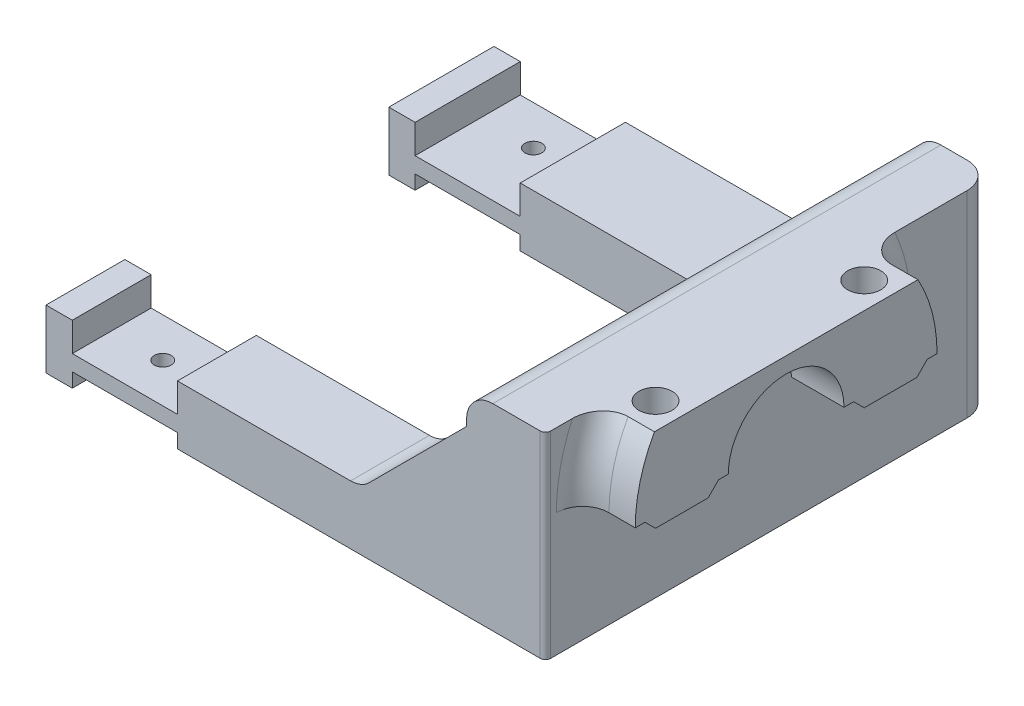
SolidWorks part; units mm, degrees
ref_plane "Plano frontal" through (0, 0, 0) normal (0, 0, 1) x (1, 0, 0)
ref_plane "Plano superior" through (0, 0, 0) normal (0, 1, 0) x (1, 0, 0)
ref_plane "Plano direito" through (0, 0, 0) normal (1, 0, 0) x (0, 0, -1)
sketch "Esboço1" plane through (0, 0, 0) normal (0, 1, 0) x (1, 0, 0)
  line L1 (10, -7.5) -> (-10, -7.5)
  line L2 (10, -7.5) -> (10, 7.5)
  line L3 (10, 7.5) -> (-10, 7.5)
  line L4 (-10, -7.5) -> (-10, 7.5)
  line L5 (10, -7.5) -> (-10, 7.5) construction
  line L6 (10, 7.5) -> (-10, -7.5) construction
  point P0 (0, 0)
  dimension "D1" = 20
  dimension "D2" = 15
extrude "Ressalto-extrusão1" add sketch "Esboço1" along normal mid plane 3
sketch "Esboço2" plane through (0, 0, 7.5) normal (0, 0, 1) x (1, 0, 0)
  line L0 (-10, 1.5) -> (-10, -1.5) construction
  line L6 (-10, -1.5) -> (10, -1.5) construction
  line L7 (-10, -4.2) -> (-15, -4.2)
  line L8 (-10, -4.2) -> (-10, 7)
  line L9 (-10, 7) -> (-15, 7)
  line L10 (-15, -4.2) -> (-15, 7)
  line L11 (-10, 1.5) -> (10, 1.5) construction
  dimension "D1" = 2.7
  dimension "D2" = 5.5
  dimension "D3" = 5
extrude "Ressalto-extrusão2" add sketch "Esboço2" against normal up to surface (15 mm away) up to face at (0, 0, -7.5)
sketch "Esboço3" plane through (0, 0, 7.5) normal (0, 0, 1) x (1, 0, 0)
  line L0 (10, 1.5) -> (10, -1.5) construction
  line L1 (10, -4.2) -> (80, -4.2)
  line L2 (10, -4.2) -> (10, 7)
  line L3 (10, 7) -> (80, 7)
  line L4 (80, -4.2) -> (80, 7)
  line L5 (-10, -1.5) -> (10, -1.5) construction
  line L6 (-10, 1.5) -> (10, 1.5) construction
  dimension "D1" = 2.7
  dimension "D2" = 5.5
  dimension "D3" = 70
extrude "Ressalto-extrusão3" add sketch "Esboço3" against normal up to surface (15 mm away) up to face at (-6.25, 0.7, -7.5)
sketch "Esboço4" plane through (0, 7, 0) normal (0, 1, 0) x (1, 0, 0)
  line L0 (-10, 77.7046) -> (-10, 57.7046) construction
  line L5 (80, 7.5) -> (65, 7.5)
  line L6 (80, 7.5) -> (80, 57.7)
  line L7 (80, 57.7) -> (65, 57.7) construction
  line L8 (65, 7.5) -> (65, 57.7)
  line L9 (65, 57.7) -> (-15, 57.7)
  line L10 (80, 57.7) -> (80, 77.7046)
  line L11 (80, 77.7046) -> (-15, 77.7046)
  line L12 (-15, 57.7) -> (-15, 77.7046)
  dimension "D1" = 50.2
  dimension "D2" = 15
  dimension "D3" = 5
  dimension "D4" = 20.0046
extrude "Ressalto-extrusão4" add sketch "Esboço4" against normal up to surface (11.2 mm away) up to face at (45, -4.2, 0)
sketch "Esboço5" plane through (0, 0, -77.7046) normal (0, 0, -1) x (-1, 0, 0)
  line L0 (-80, 7) -> (15, 7) construction
  line L1 (-10, 1.5) -> (10, 1.5)
  line L2 (-10, 1.5) -> (-10, 7)
  line L3 (-10, 7) -> (10, 7)
  line L4 (10, 1.5) -> (10, 7)
  line L5 (10, 7) -> (10, 1.5) construction
  line L6 (-80, -4.2) -> (15, -4.2) construction
  line L7 (-10, -1.5) -> (10, -1.5)
  line L8 (-10, -1.5) -> (-10, -4.2)
  line L9 (-10, -4.2) -> (10, -4.2)
  line L10 (10, -1.5) -> (10, -4.2)
  line L11 (10, -1.5) -> (10, -10.5) construction
extrude "Corte-extrusão1" cut sketch "Esboço5" against normal up to next
sketch "Esboço6" plane through (80, 0, 0) normal (1, 0, 0) x (0, 0, -1)
  line L0 (77.7046, 7) -> (-7.5, 7) construction
  line L1 (-0.4254, 7) -> (56.9746, 7)
  line L2 (-0.4254, 7) -> (-0.4254, 19.26)
  line L3 (-0.2682, 22.26) -> (56.8173, 22.26)
  line L4 (56.9746, 7) -> (56.9746, 19.26)
  line L5 (-0.4254, 19.26) -> (1.4246, 19.26) construction
  circle A0 centre (28.2746, 19.26) radius 28.7 construction
  arc A1 (-0.4254, 19.26) -> (-0.2682, 22.26) centre (28.2746, 19.26) cw
  arc A2 (56.9746, 19.26) -> (56.8173, 22.26) centre (28.2746, 19.26) ccw
  dimension "D1" = 3
extrude "Ressalto-extrusão5" add sketch "Esboço6" against normal up to surface (15 mm away) up to face at (65, 1.4, -32.6)
sketch "Esboço7" plane through (80, 0, 0) normal (1, 0, 0) x (0, 0, -1)
  line L0 (-0.4254, 19.26) -> (1.4246, 19.26)
  line L1 (3.4246, 17.26) -> (1.4246, 19.26) construction
  line L2 (1.4246, 19.26) -> (3.4246, 17.26)
  line L3 (3.4246, 17.26) -> (13.4246, 17.26)
  line L4 (13.4246, 17.26) -> (15.4246, 19.26)
  line L5 (15.4246, 19.26) -> (17.2746, 19.26)
  line L7 (56.8173, 22.26) -> (-0.2682, 22.26) construction
  line L8 (28.2746, 22.26) -> (28.2746, -4.2) construction
  line L9 (77.7046, -4.2) -> (-7.5, -4.2) construction
  line L11 (41.1246, 19.26) -> (39.2746, 19.26)
  line L12 (43.1246, 17.26) -> (41.1246, 19.26)
  line L13 (53.1246, 17.26) -> (43.1246, 17.26)
  line L14 (55.1246, 19.26) -> (53.1246, 17.26)
  line L15 (56.9746, 19.26) -> (55.1246, 19.26)
  line L16 (3.2208, 33.26) -> (53.3283, 33.26)
  arc A0 (39.2746, 19.26) -> (17.2746, 19.26) centre (28.2746, 19.26) ccw
  circle A1 centre (28.2746, 19.26) radius 11 construction
  arc A3 (-0.2682, 22.26) -> (-0.4254, 19.26) centre (28.2746, 19.26) ccw construction
  circle A7 centre (28.2746, 19.26) radius 28.7 construction
  arc A8 (3.2208, 33.26) -> (-0.4254, 19.26) centre (28.2746, 19.26) ccw
  arc A9 (56.9746, 19.26) -> (53.3283, 33.26) centre (28.2746, 19.26) ccw
  dimension "D1" = 3
extrude "Ressalto-extrusão6" add sketch "Esboço7" along normal blind 10
sketch "Esboço8" plane through (80, 0, 0) normal (-1, 0, 0) x (0, 0, 1)
  line L5 (0.2682, 22.26) -> (-56.8173, 22.26)
  line L8 (-56.8173, 22.26) -> (-38.8576, 22.26)
  line L9 (-17.6916, 22.26) -> (0.2682, 22.26)
  line L10 (-3.2208, 33.26) -> (-53.3283, 33.26)
  line L13 (-3.2208, 33.26) -> (-53.3283, 33.26)
  arc A7 (-53.3283, 33.26) -> (-56.8173, 22.26) centre (-28.2746, 19.26) ccw
  arc A8 (-17.6916, 22.26) -> (-38.8576, 22.26) centre (-28.2746, 19.26) ccw
  arc A9 (0.2682, 22.26) -> (-3.2208, 33.26) centre (-28.2746, 19.26) ccw
  arc A10 (-53.3283, 33.26) -> (-56.8173, 22.26) centre (-28.2746, 19.26) ccw
  arc A12 (0.2682, 22.26) -> (-3.2208, 33.26) centre (-28.2746, 19.26) ccw
  dimension "D1" = 0
extrude "Ressalto-extrusão7" add sketch "Esboço8" along normal up to surface (15 mm away) up to face at (65, 10.2644, -30.0047)
sketch "Esboço11" plane through (0, 17.26, 0) normal (0, -1, 0) x (1, 0, 0)
  circle A0 centre (85, -8.4246) radius 1.8
  circle A1 centre (85, -48.1246) radius 1.8
  dimension "D1" = 3.6
extrude "Corte-extrusão2" cut sketch "Esboço11" against normal through all
sketch "Esboço12" plane through (0, 33.26, 0) normal (0, 1, 0) x (1, 0, 0)
  circle A0 centre (85, 48.1246) radius 3.15
  circle A1 centre (85, 8.4246) radius 3.15
  dimension "D1" = 6.3
extrude "Corte-extrusão3" cut sketch "Esboço12" against normal blind 5
sketch "Esboço13" plane through (65, 0, 0) normal (-1, 0, 0) x (0, 0, 1)
  line L0 (0.4254, 7) -> (7.5, 7)
  line L1 (7.5, 7) -> (7.5, 33.26)
  line L2 (7.5, 33.26) -> (-3.2208, 33.26)
  line L3 (-3.2208, 33.26) -> (-53.3283, 33.26) construction
  line L4 (0.4254, 7) -> (0.4254, 19.26)
  line L5 (-56.9746, 7) -> (-77.7046, 7)
  line L6 (-77.7046, 7) -> (-77.7046, 33.26)
  line L7 (-77.7046, 33.26) -> (-53.3283, 33.26)
  line L8 (-56.9746, 7) -> (-56.9746, 19.26)
  arc A0 (0.4254, 19.26) -> (-3.2208, 33.26) centre (-28.2746, 19.26) ccw construction
  arc A1 (-53.3283, 33.26) -> (-56.9746, 19.26) centre (-28.2746, 19.26) ccw
  arc A2 (0.4254, 19.26) -> (-3.2208, 33.26) centre (-28.2746, 19.26) ccw
extrude "Ressalto-extrusão8" add sketch "Esboço13" against normal up to surface (15 mm away) up to face at (80, 14.0956, -29.7918)
chamfer "Chanfro1" distance 20 angle 45 1 edges at (65, 7, 0)
fillet "Filete1" radius 5 3 edges at (80, 26.4935, -56.048) (80, 26.4935, -0.5011) (65, 33.26, -35.1023)
fillet "Filete4" radius 1 1 edges at (80, 14.53, 7.5)
fillet "Filete5" radius 5 3 edges at (45, 7, -67.7023) (45, 7, 0) (80, 14.53, -77.7046)
sketch "Esboço14" plane through (0, 1.5, 0) normal (0, 1, 0) x (1, 0, 0)
  circle A0 centre (-0.3, 0) radius 1.6
  circle A1 centre (0, 70.2046) radius 1.6
  dimension "D1" = 3.2
  dimension "D2" = 3.2
extrude "Corte-extrusão4" cut sketch "Esboço14" against normal up to next
